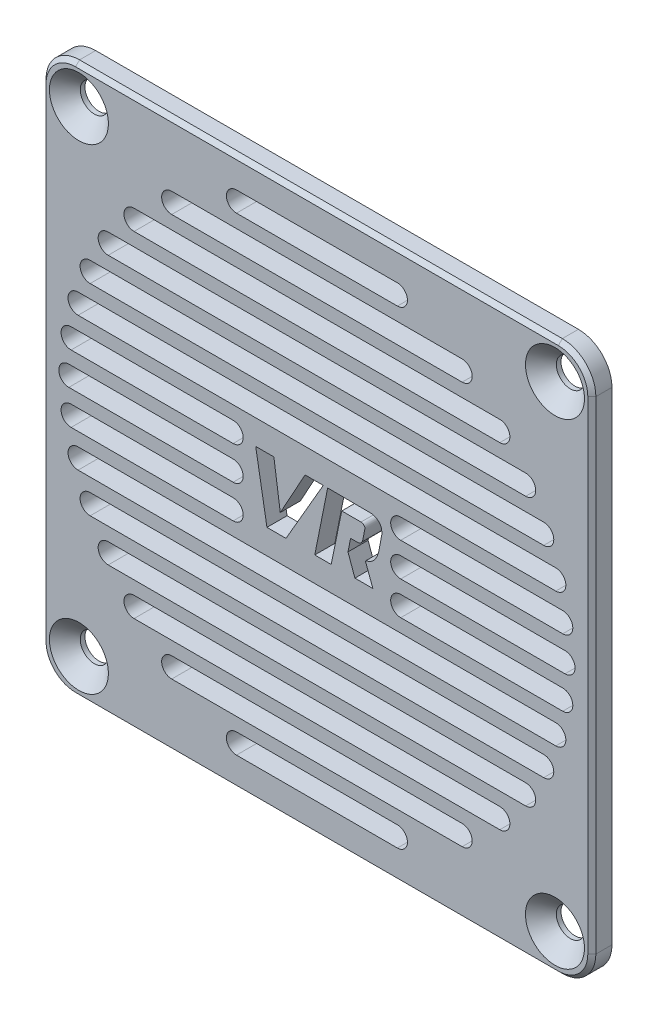
SolidWorks part; units mm, degrees
ref_plane "Front Plane" through (0, 0, 0) normal (0, 0, 1) x (1, 0, 0)
ref_plane "Top Plane" through (0, 0, 0) normal (0, 1, 0) x (1, 0, 0)
ref_plane "Right Plane" through (0, 0, 0) normal (1, 0, 0) x (0, 0, -1)
sketch "Sketch1" plane through (0, 0, 0) normal (0, 0, 1) x (1, 0, 0)
  line L0 (41, 36) -> (41, -36)
  line L1 (36, -41) -> (-36, -41)
  line L2 (-41, -36) -> (-41, 36)
  line L3 (-36, 41) -> (36, 41)
  line L4 (0, 6.288) -> (0, 0) construction
  line L5 (0, 0) -> (5.6688, 0) construction
  line L6 (102.5259, 3.6525) -> (240.1283, 3.6525) construction
  line L7 (237.3735, 205.8696) -> (682.0402, 205.8696) construction
  line L8 (155.5388, 233.4582) -> (600.2055, 233.4582) construction
  circle A0 centre (0, 0) radius 10.5 construction
  circle A3 centre (35.5, -35.5) radius 2.1
  circle A4 centre (-35.5, -35.5) radius 2.1
  circle A5 centre (-35.5, 35.5) radius 2.1
  circle A6 centre (35.5, 35.5) radius 2.1
  arc A7 (41, 36) -> (36, 41) centre (36, 36) ccw
  arc A8 (36, -41) -> (41, -36) centre (36, -36) ccw
  arc A9 (-41, -36) -> (-36, -41) centre (-36, -36) ccw
  arc A10 (-36, 41) -> (-41, 36) centre (-36, 36) ccw
  circle A11 centre (0, 0) radius 19.5 construction
  dimension "D1" = 39
  dimension "D2" = 21
  dimension "D5" = 5
  dimension "D6" = 4.2
  dimension "D3" = 82
  dimension "D4" = 82
  dimension "D7" = 71
  dimension "D8" = 71
extrude "Base" add sketch "Sketch1" along normal blind 3
chamfer "Chamfer1" distance 2.3 angle 45 4 edges at (37.6, -35.5, 3) (-33.4, -35.5, 3) (37.6, 35.5, 3) (-33.4, 35.5, 3)
sketch "Sketch3" plane through (0, 0, 3) normal (0, 0, 1) x (1, 0, 0)
  circle A0 centre (0, 0) radius 10.5 construction
  line B0 (0.9438, 4.8073) -> (-1.7703, 4.8073)
  line B1 (3.7035, 2.8898) -> (6.5735, 2.8898)
  line B2 (6.5735, 2.8898) -> (6.8393, 2.8463) construction
  line B3 (6.8393, 2.8463) -> (7.0318, 2.6813) construction
  line B4 (7.0318, 2.6813) -> (7.1365, 2.5072) construction
  line B5 (7.1365, 2.5072) -> (7.1365, 2.2404) construction
  line B6 (5.021, 0.0136) -> (6.1671, 0.0136)
  line B7 (6.1671, 0.0136) -> (6.4334, 0.0999) construction
  line B8 (6.4334, 0.0999) -> (6.6026, 0.2489) construction
  line B9 (6.6026, 0.2489) -> (6.7446, 0.4146) construction
  line B10 (6.7446, 0.4146) -> (6.8393, 0.6984) construction
  line B11 (6.8393, 0.6984) -> (7.1365, 2.2404) construction
  line B12 (4.6314, -1.9349) -> (5.021, 0.0136)
  line B13 (-9.1314, 4.8073) -> (-6.4211, 4.8073)
  line B14 (-6.4211, 4.8073) -> (-5.4671, -1.8998)
  line B15 (-5.4671, -1.8998) -> (-1.7703, 4.8073)
  line B16 (0.9438, 4.8073) -> (-4.6161, -4.8111)
  line B17 (-4.6161, -4.8111) -> (-7.4548, -4.8111)
  line B18 (-7.4548, -4.8111) -> (-9.1314, 4.8073)
  line B19 (1.6005, 4.8073) -> (8.0334, 4.7764)
  line B20 (7.2293, -1.8111) -> (8.3427, -4.8111)
  line B21 (8.3427, -4.8111) -> (5.6631, -4.8111)
  line B22 (5.6631, -4.8111) -> (4.6314, -1.9349)
  line B23 (3.7035, 2.8898) -> (2.1262, -4.8111)
  line B24 (2.1262, -4.8111) -> (-0.3232, -4.8111)
  line B25 (-0.3232, -4.8111) -> (1.6005, 4.8073)
  line B26 (9.6784, 2.8463) -> (9.2292, 0.4146)
  spline B27 degree 3 poles (9.2292, 0.4146) (9.1202, 0.0172) (8.9153, -0.5548) (8.4464, -1.1602) (7.9426, -1.5631) (7.4993, -1.705) (7.2293, -1.8111) knots 0 0 0 0 0.394089 0.566272 0.722136 1 1 1 1
  spline B28 degree 3 poles (9.6784, 2.8463) (9.687, 2.9892) (9.6873, 3.2192) (9.6341, 3.5736) (9.531, 3.877) (9.319, 4.175) (9.0589, 4.4168) (8.7482, 4.6112) (8.4048, 4.733) (8.1636, 4.7706) (8.0334, 4.7764) knots 0 0 0 0 0.150298 0.240096 0.375313 0.481557 0.62039 0.745312 0.863341 1 1 1 1
  spline B29 degree 3 poles (6.5735, 2.8898) (6.6399, 2.879) (6.7064, 2.8681) (6.7728, 2.8572) (6.7866, 2.8549) (6.8142, 2.8504) (6.8556, 2.8324) (6.8768, 2.8142) (6.8874, 2.8051) (6.9195, 2.7776) (6.9516, 2.7501) (6.9837, 2.7226) (6.9932, 2.7144) (7.0122, 2.6981) (7.0386, 2.67) (7.0515, 2.6485) (7.058, 2.6378) (7.0754, 2.6088) (7.0929, 2.5797) (7.1103, 2.5507) (7.1168, 2.5399) (7.1298, 2.5183) (7.1365, 2.4782) (7.1365, 2.453) (7.1365, 2.4405) (7.1365, 2.396) (7.1365, 2.3515) (7.1365, 2.3071) (7.1365, 2.2923) (7.1365, 2.2628) (7.1322, 2.2183) (7.1266, 2.1894) (7.1239, 2.1749) (7.0337, 1.7072) (6.9436, 1.2395) (6.8534, 0.7718) (6.8503, 0.7555) (6.844, 0.723) (6.8314, 0.6746) (6.8209, 0.6432) (6.8156, 0.6274) (6.7998, 0.5801) (6.784, 0.5328) (6.7683, 0.4855) (6.7638, 0.4721) (6.7549, 0.4454) (6.7366, 0.4053) (6.7183, 0.3838) (6.7091, 0.3731) (6.6854, 0.3455) (6.6617, 0.3179) (6.6381, 0.2903) (6.6301, 0.2809) (6.6141, 0.2623) (6.5879, 0.236) (6.5695, 0.2197) (6.5603, 0.2116) (6.5321, 0.1868) (6.5039, 0.1619) (6.4757, 0.1371) (6.4653, 0.128) (6.4447, 0.1099) (6.406, 0.091) (6.3799, 0.0825) (6.3668, 0.0783) (6.3002, 0.0567) (6.2336, 0.0352) (6.1671, 0.0136) knots 0 0 0 0 0.056598 0.056598 0.056598 0.068353 0.080109 0.091864 0.091864 0.091864 0.127378 0.127378 0.127378 0.137906 0.148433 0.158961 0.158961 0.158961 0.187427 0.187427 0.187427 0.198008 0.208589 0.21917 0.21917 0.21917 0.256543 0.256543 0.256543 0.268944 0.281346 0.293747 0.293747 0.293747 0.694048 0.694048 0.694048 0.707988 0.721929 0.735869 0.735869 0.735869 0.777781 0.777781 0.777781 0.789642 0.801504 0.813365 0.813365 0.813365 0.843938 0.843938 0.843938 0.854271 0.864604 0.874936 0.874936 0.874936 0.906514 0.906514 0.906514 0.91807 0.929625 0.941181 0.941181 0.941181 1 1 1 1
  dimension "D1" = 21
sketch_block_instance "Block1-1"
sketch_block "Block1" parameters "D1"=1.6237
extrude "Logo" cut sketch "Sketch3" against normal through all
sketch "Sketch4" plane through (0, 0, 3) normal (0, 0, 1) x (1, 0, 0)
  line L0 (-33.8231, 15) -> (33.8231, 15) construction
  line L1 (11, -5.7242) -> (-11, -5.7242) construction
  line L2 (0, 0) -> (-7.3146, 0) construction
  line L3 (11, -5.7242) -> (11, 5.7242) construction
  line L4 (11, 5.7242) -> (-11, 5.7242) construction
  line L5 (-11, -5.7242) -> (-11, 5.7242) construction
  line L6 (11, -5.7242) -> (-11, 5.7242) construction
  line L7 (11, 5.7242) -> (-11, -5.7242) construction
  line L8 (-33.8231, 16.5) -> (33.8231, 16.5)
  line L9 (-33.8231, 13.5) -> (33.8231, 13.5)
  line L10 (-35.623, 10) -> (35.623, 10) construction
  line L11 (-35.623, 11.5) -> (35.623, 11.5)
  line L12 (-35.623, 8.5) -> (35.623, 8.5)
  line L13 (-33.8231, -15) -> (33.8231, -15) construction
  line L14 (-33.8231, -13.5) -> (33.8231, -13.5)
  line L15 (-33.8231, -16.5) -> (33.8231, -16.5)
  line L16 (-35.623, -10) -> (35.623, -10) construction
  line L17 (-35.623, -8.5) -> (35.623, -8.5)
  line L18 (-35.623, -11.5) -> (35.623, -11.5)
  line L19 (12.5, 5) -> (36.6606, 5) construction
  line L20 (12.5, 6.5) -> (36.6606, 6.5)
  line L21 (12.5, 3.5) -> (36.6606, 3.5)
  line L22 (12.5, -5) -> (36.6606, -5) construction
  line L23 (12.5, -3.5) -> (36.6606, -3.5)
  line L24 (12.5, -6.5) -> (36.6606, -6.5)
  line L25 (-36.6606, 5) -> (-12.5, 5) construction
  line L26 (-36.6606, 6.5) -> (-12.5, 6.5)
  line L27 (-36.6606, 3.5) -> (-12.5, 3.5)
  line L28 (-36.6606, -5) -> (-12.5, -5) construction
  line L29 (-36.6606, -3.5) -> (-12.5, -3.5)
  line L30 (-36.6606, -6.5) -> (-12.5, -6.5)
  line L31 (0, 0) -> (0, 7.3736) construction
  line L32 (-37, 0) -> (-12.5, 0) construction
  line L33 (-37, 1.5) -> (-12.5, 1.5)
  line L34 (-37, -1.5) -> (-12.5, -1.5)
  line L35 (12.5, 0) -> (37, 0) construction
  line L36 (12.5, 1.5) -> (37, 1.5)
  line L37 (12.5, -1.5) -> (37, -1.5)
  line L38 (-31.1288, 20) -> (31.1288, 20) construction
  line L39 (-31.1288, 21.5) -> (31.1288, 21.5)
  line L40 (-31.1288, 18.5) -> (31.1288, 18.5)
  line L41 (-27.2764, 25) -> (27.2764, 25) construction
  line L42 (-27.2764, 26.5) -> (27.2764, 26.5)
  line L43 (-27.2764, 23.5) -> (27.2764, 23.5)
  line L44 (-21.6564, 30) -> (21.6564, 30) construction
  line L45 (-21.6564, 31.5) -> (21.6564, 31.5)
  line L46 (-21.6564, 28.5) -> (21.6564, 28.5)
  line L47 (-12, 35) -> (12, 35) construction
  line L48 (-12, 36.5) -> (12, 36.5)
  line L49 (-12, 33.5) -> (12, 33.5)
  line L50 (-31.1288, -20) -> (31.1288, -20) construction
  line L51 (-31.1288, -21.5) -> (31.1288, -21.5)
  line L52 (-31.1288, -18.5) -> (31.1288, -18.5)
  line L53 (-27.2764, -25) -> (27.2764, -25) construction
  line L54 (-27.2764, -26.5) -> (27.2764, -26.5)
  line L55 (-27.2764, -23.5) -> (27.2764, -23.5)
  line L56 (-21.6564, -30) -> (21.6564, -30) construction
  line L57 (-21.6564, -31.5) -> (21.6564, -31.5)
  line L58 (-21.6564, -28.5) -> (21.6564, -28.5)
  line L59 (-12, -35) -> (12, -35) construction
  line L60 (-12, -36.5) -> (12, -36.5)
  line L61 (-12, -33.5) -> (12, -33.5)
  circle A0 centre (0, 0) radius 38.5 construction
  circle A1 centre (0, 0) radius 10.5 construction
  arc A2 (-33.8231, 16.5) -> (-33.8231, 13.5) centre (-33.8231, 15) ccw
  arc A3 (33.8231, 13.5) -> (33.8231, 16.5) centre (33.8231, 15) ccw
  arc A4 (-35.623, 11.5) -> (-35.623, 8.5) centre (-35.623, 10) ccw
  arc A5 (35.623, 8.5) -> (35.623, 11.5) centre (35.623, 10) ccw
  arc A6 (-33.8231, -13.5) -> (-33.8231, -16.5) centre (-33.8231, -15) ccw
  arc A7 (33.8231, -16.5) -> (33.8231, -13.5) centre (33.8231, -15) ccw
  arc A8 (-35.623, -8.5) -> (-35.623, -11.5) centre (-35.623, -10) ccw
  arc A9 (35.623, -11.5) -> (35.623, -8.5) centre (35.623, -10) ccw
  arc A10 (12.5, 6.5) -> (12.5, 3.5) centre (12.5, 5) ccw
  arc A11 (36.6606, 3.5) -> (36.6606, 6.5) centre (36.6606, 5) ccw
  arc A12 (12.5, -3.5) -> (12.5, -6.5) centre (12.5, -5) ccw
  arc A13 (36.6606, -6.5) -> (36.6606, -3.5) centre (36.6606, -5) ccw
  arc A14 (-36.6606, 6.5) -> (-36.6606, 3.5) centre (-36.6606, 5) ccw
  arc A15 (-12.5, 3.5) -> (-12.5, 6.5) centre (-12.5, 5) ccw
  arc A16 (-36.6606, -3.5) -> (-36.6606, -6.5) centre (-36.6606, -5) ccw
  arc A17 (-12.5, -6.5) -> (-12.5, -3.5) centre (-12.5, -5) ccw
  arc A18 (-37, 1.5) -> (-37, -1.5) centre (-37, 0) ccw
  arc A19 (-12.5, -1.5) -> (-12.5, 1.5) centre (-12.5, 0) ccw
  arc A20 (12.5, 1.5) -> (12.5, -1.5) centre (12.5, 0) ccw
  arc A21 (37, -1.5) -> (37, 1.5) centre (37, 0) ccw
  arc A22 (-31.1288, 21.5) -> (-31.1288, 18.5) centre (-31.1288, 20) ccw
  arc A23 (31.1288, 18.5) -> (31.1288, 21.5) centre (31.1288, 20) ccw
  arc A24 (-27.2764, 26.5) -> (-27.2764, 23.5) centre (-27.2764, 25) ccw
  arc A25 (27.2764, 23.5) -> (27.2764, 26.5) centre (27.2764, 25) ccw
  arc A26 (-21.6564, 31.5) -> (-21.6564, 28.5) centre (-21.6564, 30) ccw
  arc A27 (21.6564, 28.5) -> (21.6564, 31.5) centre (21.6564, 30) ccw
  arc A28 (-12, 36.5) -> (-12, 33.5) centre (-12, 35) ccw
  arc A29 (12, 33.5) -> (12, 36.5) centre (12, 35) ccw
  arc A30 (-31.1288, -21.5) -> (-31.1288, -18.5) centre (-31.1288, -20) cw
  arc A31 (31.1288, -18.5) -> (31.1288, -21.5) centre (31.1288, -20) cw
  arc A32 (-27.2764, -26.5) -> (-27.2764, -23.5) centre (-27.2764, -25) cw
  arc A33 (27.2764, -23.5) -> (27.2764, -26.5) centre (27.2764, -25) cw
  arc A34 (-21.6564, -31.5) -> (-21.6564, -28.5) centre (-21.6564, -30) cw
  arc A35 (21.6564, -28.5) -> (21.6564, -31.5) centre (21.6564, -30) cw
  arc A36 (-12, -36.5) -> (-12, -33.5) centre (-12, -35) cw
  arc A37 (12, -33.5) -> (12, -36.5) centre (12, -35) cw
  point P6 (0, 15)
  point P16 (0, 10)
  point P23 (0, -15)
  point P30 (0, -10)
  point P37 (24.5803, 5)
  point P44 (24.5803, -5)
  point P51 (-24.5803, 5)
  point P58 (-24.5803, -5)
  point P68 (0, 20)
  point P71 (-24.75, 0)
  point P78 (24.75, 0)
  point P89 (0, 25)
  point P96 (0, 30)
  point P103 (0, 35)
  point P114 (0, -20)
  point P121 (0, -25)
  point P128 (0, -30)
  point P135 (0, -35)
  point P155 (0, 0)
  dimension "D1" = 77
  dimension "D2" = 21
  dimension "D4" = 3
  dimension "D5" = 3
  dimension "D3" = 22
  dimension "D6" = 3
  dimension "D7" = 3
  dimension "D8" = 3
  dimension "D9" = 3
  dimension "D10" = 2
  dimension "D11" = 2
  dimension "D12" = 2
  dimension "D13" = 2
  dimension "D14" = 2
  dimension "D15" = 2
  dimension "D16" = 2
  dimension "D17" = 2
extrude "Holes" cut sketch "Sketch4" against normal through all contours L9 A3 L8 A2 | L12 A5 L11 A4 | L27 A15 L26 A14 | L30 A17 L29 A16 | L18 A9 L17 A8 | L15 A7 L14 A6 | L24 A13 L23 A12 | L21 A11 L20 A10 | L34 A19 L33 A18 | L37 A21 L36 A20 | L40 A23 L39 A22 | L43 A25 L42 A24 | L46 A27 L45 A26 | L49 A29 L48 A28 | A31 L52 A30 L51 | A33 L55 A32 L54 | A35 L58 A34 L57 | A37 L61 A36 L60
chamfer "Chamfer2" distance 0.6 angle 45 8 edges at (0, -41, 3) (-39.5355, -39.5355, 3) (39.5355, -39.5355, 3) (-41, 0, 3) (41, 0, 3) (-39.5355, 39.5355, 3) (39.5355, 39.5355, 3) (0, 41, 3)
equation "\"D4\"=80"
equation "\"D3@Sketch1\"=\"D4@Sketch1\""
